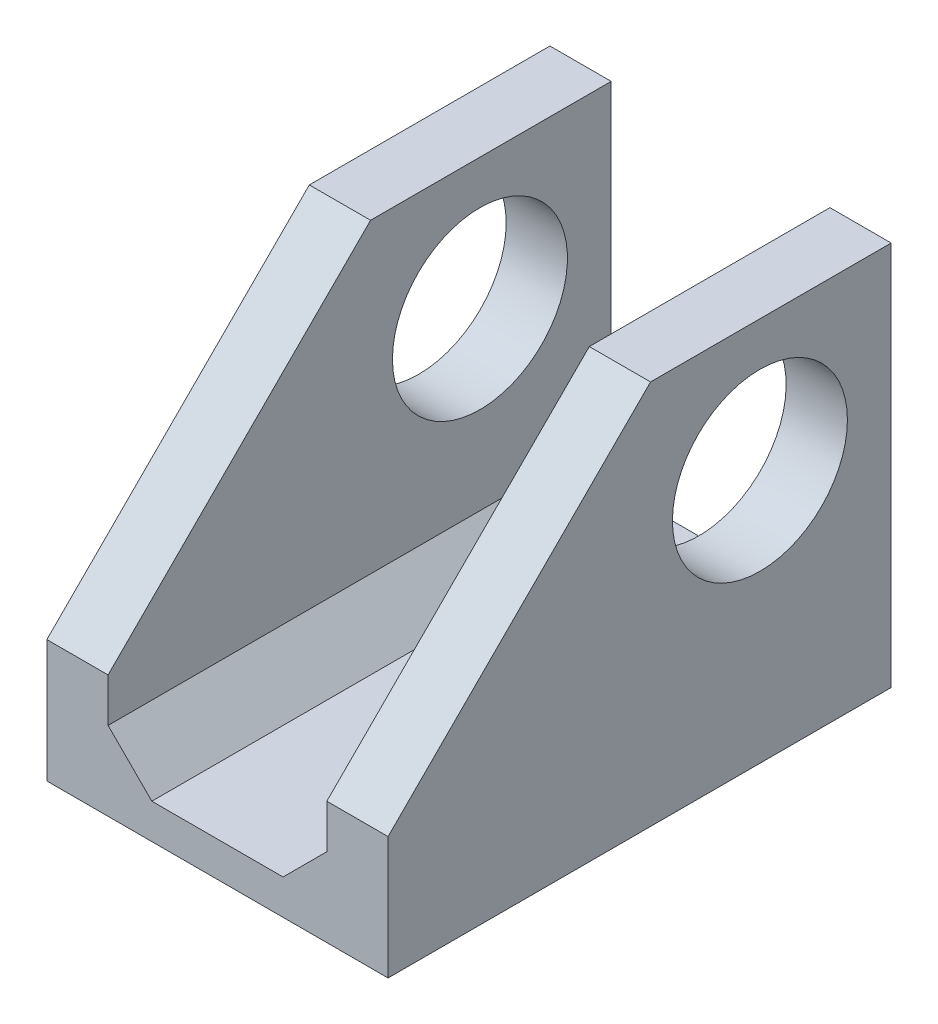
SolidWorks part; units mm, degrees
ref_plane "Front Plane" through (0, 0, 0) normal (0, 0, 1) x (1, 0, 0)
ref_plane "Top Plane" through (0, 0, 0) normal (0, 1, 0) x (1, 0, 0)
ref_plane "Right Plane" through (0, 0, 0) normal (1, 0, 0) x (0, 0, -1)
sketch "Sketch2" plane through (0, 0, 0) normal (0, 0, 1) x (1, 0, 0)
  line L0 (0, 0) -> (-50, 0)
  line L1 (-50, 0) -> (-50, 80)
  line L2 (-50, 80) -> (-64, 80)
  line L3 (-64, 80) -> (-64, -8)
  line L4 (-64, -8) -> (14, -8)
  line L5 (14, -8) -> (14, 80)
  line L6 (14, 80) -> (0, 80)
  line L7 (0, 80) -> (0, 0)
  point P3 (-49.8553, -8)
  dimension "D1" = 14
  dimension "D2" = 14
  dimension "D3" = 80
  dimension "D4" = 8
  dimension "D5" = 50
extrude "Boss-Extrude1" add sketch "Sketch2" against normal blind 30 and the other way blind 85
sketch "Sketch3" plane through (0, 0, 0) normal (1, 0, 0) x (0, 0, -1)
  circle A0 centre (0, 50) radius 20
  point P2 (0, 0)
  dimension "D1" = 40
  dimension "D2" = 50
extrude "Cut-Extrude1" cut sketch "Sketch3" along normal through all both and the other way through all
chamfer "Chamfer1" distance 10 angle 45 2 edges at (-50, 0, 27.5) (0, 0, 27.5)
chamfer "Chamfer2" distance 60 angle 45 2 edges at (7, 80, 85) (-57, 80, 85)
sketch "Sketch4" plane through (0, -8, 0) normal (0, -1, 0) x (1, 0, 0)
  line L0 (-64, 85) -> (-104, 0)
  line L1 (-104, 0) -> (-104, -30)
  line L2 (-104, -30) -> (-64, -30)
  line L3 (-64, -30) -> (-64, 85)
  line L4 (14, 85) -> (14, -30)
  line L5 (14, -30) -> (54, -30)
  line L6 (54, -30) -> (54, 0)
  line L7 (54, 0) -> (14, 85)
  point P10 (0, 0)
  point P13 (0, 0)
  dimension "D1" = 40
  dimension "D2" = 40
